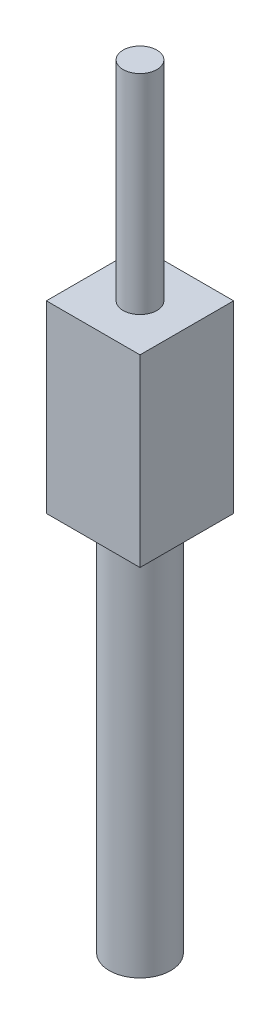
SolidWorks part; units mm, degrees
ref_plane "Front Plane" through (0, 0, 0) normal (0, 0, 1) x (1, 0, 0)
ref_plane "Top Plane" through (0, 0, 0) normal (0, 1, 0) x (1, 0, 0)
ref_plane "Right Plane" through (0, 0, 0) normal (1, 0, 0) x (0, 0, -1)
sketch "Sketch1" plane through (0, 0, 0) normal (0, 1, 0) x (1, 0, 0)
  circle A0 centre (0, 0) radius 5
  dimension "D1" = 10
extrude "Boss-Extrude1" add sketch "Sketch1" along normal blind 62
sketch "Sketch3" plane through (0, 62, 0) normal (0, 1, 0) x (1, 0, 0)
  line L1 (-7.625, -7.625) -> (7.625, -7.625)
  line L2 (-7.625, -7.625) -> (-7.625, 7.625)
  line L3 (-7.625, 7.625) -> (7.625, 7.625)
  line L4 (7.625, -7.625) -> (7.625, 7.625)
  line L5 (-7.625, -7.625) -> (7.625, 7.625) construction
  line L6 (-7.625, 7.625) -> (7.625, -7.625) construction
  point P0 (0, 0)
  dimension "D1" = 15.25
  dimension "D2" = 15.25
extrude "Boss-Extrude2" add sketch "Sketch3" along normal blind 30
sketch "Sketch4" plane through (0, 92, 0) normal (0, 1, 0) x (1, 0, 0)
  circle A0 centre (0, 0) radius 2.75
  dimension "D1" = 5.5
sketch "Sketch5" plane through (0, 0, 0) normal (0, -1, 0) x (1, 0, 0)
  circle A0 centre (0, 0) radius 3
  dimension "D1" = 6
extrude "Cut-Extrude1" cut sketch "Sketch5" against normal blind 10
fillet "Fillet1" [suppressed] radius 4
extrude "Boss-Extrude3" add sketch "Sketch4" along normal blind 34
